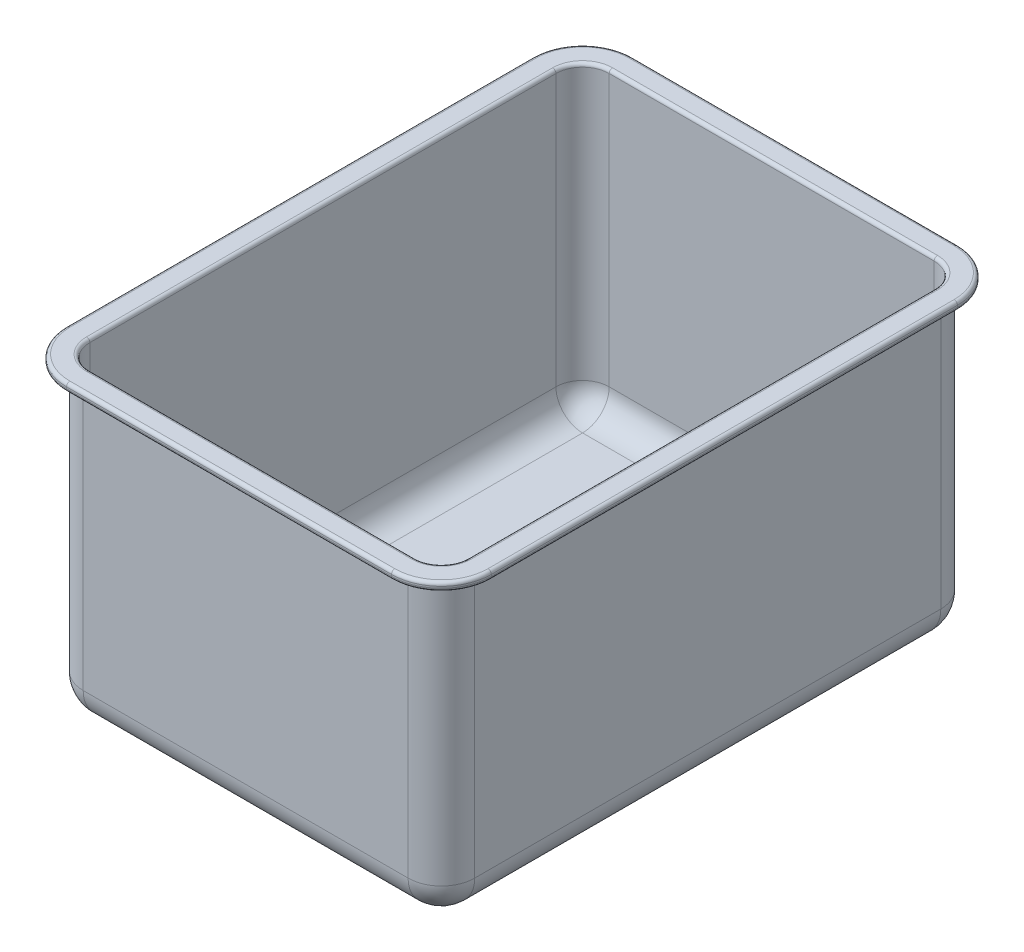
SolidWorks part; units mm, degrees
ref_plane "Front Plane" through (0, 0, 0) normal (0, 0, 1) x (1, 0, 0)
ref_plane "Top Plane" through (0, 0, 0) normal (0, 1, 0) x (1, 0, 0)
ref_plane "Right Plane" through (0, 0, 0) normal (1, 0, 0) x (0, 0, -1)
sketch "Sketch1" plane through (0, 0, 0) normal (0, 1, 0) x (1, 0, 0)
  line L1 (-74.676, -101.6) -> (74.676, -101.6)
  line L2 (-74.676, -101.6) -> (-74.676, 101.6)
  line L3 (-74.676, 101.6) -> (74.676, 101.6)
  line L4 (74.676, -101.6) -> (74.676, 101.6)
  line L5 (-74.676, -101.6) -> (74.676, 101.6) construction
  line L6 (-74.676, 101.6) -> (74.676, -101.6) construction
  point P0 (0, 0)
  dimension "D1" = 203.2
  dimension "D2" = 149.352
extrude "Boss-Extrude1" add sketch "Sketch1" along normal blind 114.3
fillet "Fillet1" radius 12.7 8 edges at (0, 0, -101.6) (-74.676, 0, 0) (0, 0, 101.6) (74.676, 0, 0) (-74.676, 57.15, -101.6) (-74.676, 57.15, 101.6) (74.676, 57.15, -101.6) (74.676, 57.15, 101.6)
shell "Shell1" thickness 2.54
sketch "Sketch2" plane through (0, 114.3, 0) normal (0, 1, 0) x (1, 0, 0)
  line L0 (-74.676, 88.9) -> (-74.676, -88.9) construction
  line L1 (-61.976, -101.6) -> (61.976, -101.6) construction
  line L2 (74.676, -88.9) -> (74.676, 88.9) construction
  line L3 (61.976, 101.6) -> (-61.976, 101.6) construction
  line L4 (-72.136, 88.9) -> (-72.136, -88.9) construction
  line L5 (-61.976, -99.06) -> (61.976, -99.06) construction
  line L6 (72.136, -88.9) -> (72.136, 88.9) construction
  line L7 (61.976, 99.06) -> (-61.976, 99.06) construction
  line L8 (-74.676, 88.9) -> (-74.676, -88.9) construction
  line L9 (-61.976, -101.6) -> (61.976, -101.6) construction
  line L10 (74.676, -88.9) -> (74.676, 88.9) construction
  line L11 (61.976, 101.6) -> (-61.976, 101.6) construction
  line L12 (-72.136, 88.9) -> (-72.136, -88.9)
  line L13 (-61.976, -99.06) -> (61.976, -99.06)
  line L14 (72.136, -88.9) -> (72.136, 88.9)
  line L15 (61.976, 99.06) -> (-61.976, 99.06)
  line L16 (61.976, 107.95) -> (-61.976, 107.95)
  line L17 (-81.026, 88.9) -> (-81.026, -88.9)
  line L18 (-61.976, -107.95) -> (61.976, -107.95)
  line L19 (81.026, -88.9) -> (81.026, 88.9)
  arc A0 (-74.676, -88.9) -> (-61.976, -101.6) centre (-61.976, -88.9) ccw construction
  arc A1 (61.976, -101.6) -> (74.676, -88.9) centre (61.976, -88.9) ccw construction
  arc A2 (74.676, 88.9) -> (61.976, 101.6) centre (61.976, 88.9) ccw construction
  arc A3 (-61.976, 101.6) -> (-74.676, 88.9) centre (-61.976, 88.9) ccw construction
  arc A4 (-61.976, 99.06) -> (-72.136, 88.9) centre (-61.976, 88.9) ccw construction
  arc A5 (-72.136, -88.9) -> (-61.976, -99.06) centre (-61.976, -88.9) ccw construction
  arc A6 (61.976, -99.06) -> (72.136, -88.9) centre (61.976, -88.9) ccw construction
  arc A7 (72.136, 88.9) -> (61.976, 99.06) centre (61.976, 88.9) ccw construction
  arc A8 (-74.676, -88.9) -> (-61.976, -101.6) centre (-61.976, -88.9) ccw construction
  arc A9 (61.976, -101.6) -> (74.676, -88.9) centre (61.976, -88.9) ccw construction
  arc A10 (74.676, 88.9) -> (61.976, 101.6) centre (61.976, 88.9) ccw construction
  arc A11 (-61.976, 101.6) -> (-74.676, 88.9) centre (-61.976, 88.9) ccw construction
  arc A12 (-61.976, 99.06) -> (-72.136, 88.9) centre (-61.976, 88.9) ccw
  arc A13 (-72.136, -88.9) -> (-61.976, -99.06) centre (-61.976, -88.9) ccw
  arc A14 (61.976, -99.06) -> (72.136, -88.9) centre (61.976, -88.9) ccw
  arc A15 (72.136, 88.9) -> (61.976, 99.06) centre (61.976, 88.9) ccw
  arc A16 (-61.976, 107.95) -> (-81.026, 88.9) centre (-61.976, 88.9) ccw
  arc A17 (-81.026, -88.9) -> (-61.976, -107.95) centre (-61.976, -88.9) ccw
  arc A18 (61.976, -107.95) -> (81.026, -88.9) centre (61.976, -88.9) ccw
  arc A19 (81.026, 88.9) -> (61.976, 107.95) centre (61.976, 88.9) ccw
  dimension "D1" = 6.35
extrude "Boss-Extrude2" add sketch "Sketch2" along normal blind 3.175
fillet "Fillet2" radius 1.27 24 edges at (-75.4464, 117.475, 102.3704) (-81.026, 117.475, 0) (-75.4464, 117.475, -102.3704) (0, 117.475, -107.95) (75.4464, 117.475, -102.3704) (81.026, 117.475, 0) (75.4464, 117.475, 102.3704) (-75.4464, 114.3, 102.3704) (-81.026, 114.3, 0) (-75.4464, 114.3, -102.3704) (0, 114.3, -107.95) (75.4464, 114.3, -102.3704) (81.026, 114.3, 0) (75.4464, 114.3, 102.3704) (0, 117.475, 107.95) (0, 114.3, 107.95) (69.1602, 117.475, 96.0842) (0, 117.475, 99.06) (-69.1602, 117.475, 96.0842) (-72.136, 117.475, 0) (-69.1602, 117.475, -96.0842) (0, 117.475, -99.06) (69.1602, 117.475, -96.0842) (72.136, 117.475, 0)
